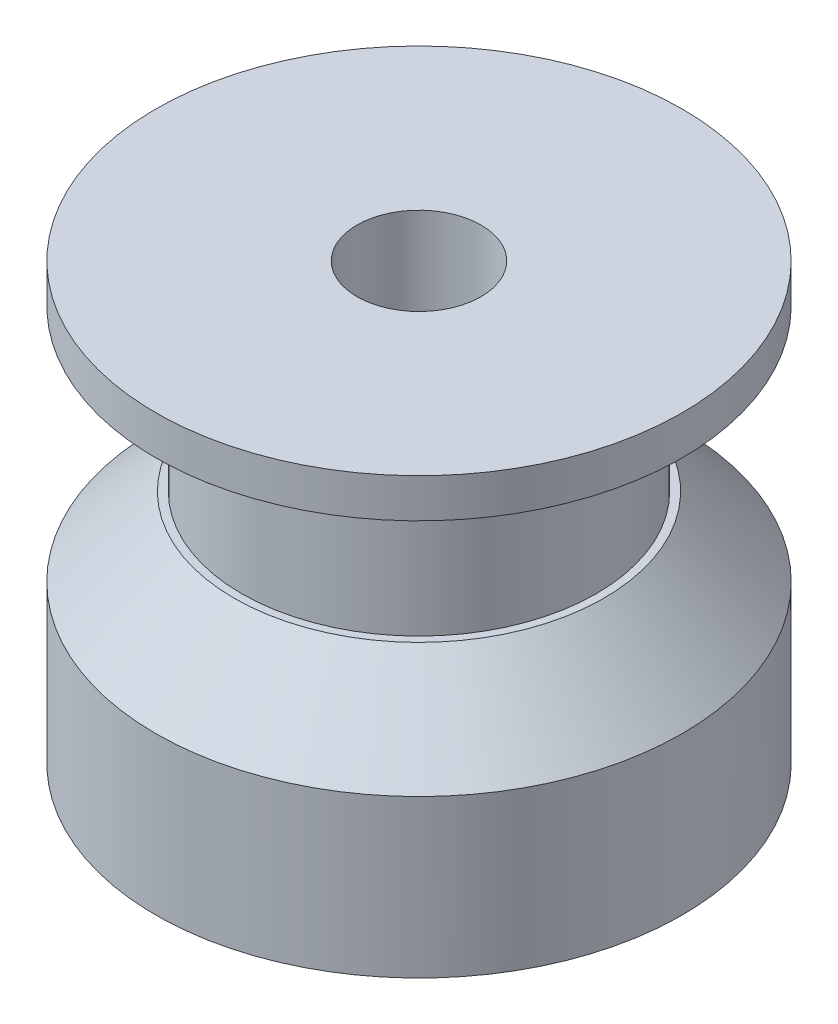
SolidWorks part; units mm, degrees
material "6061 Alloy"
ref_plane "Front Plane" through (0, 0, 0) normal (0, 0, 1) x (1, 0, 0)
ref_plane "Top Plane" through (0, 0, 0) normal (0, 1, 0) x (1, 0, 0)
ref_plane "Right Plane" through (0, 0, 0) normal (1, 0, 0) x (0, 0, -1)
sketch "Sketch1" plane through (0, 0, 0) normal (0, 0, 1) x (1, 0, 0)
  line L0 (0, 0) -> (0, 16.6392) construction
  line L1 (0, 0) -> (31.4533, 0) construction
  line L2 (1.5875, 0) -> (1.5875, 11.1252)
  line L3 (1.5875, 11.1252) -> (6.73, 11.1252)
  line L4 (6.73, 11.1252) -> (6.73, 10.1252)
  line L5 (6.73, 10.1252) -> (4.5339, 10.1252)
  line L6 (4.5339, 10.1252) -> (4.5339, 6.0198)
  line L7 (4.5339, 6.0198) -> (6.731, 6.0198)
  line L8 (6.731, 6.0198) -> (6.731, 0)
  line L9 (6.731, 0) -> (1.5875, 0)
  dimension "D1" = 6.731
  dimension "D2" = 1.5875
  dimension "D3" = 11.1252
  dimension "D4" = 1
  dimension "D5" = 5.1054
  dimension "D6" = 4.5339
  dimension "D7" = 6.73
revolve "Revolve1" add sketch "Sketch1" angle 360 about L0
chamfer "Chamfer1" distance 2 angle 45 1 edges at (0, 6.0198, -6.731)
hole_wizard "M2x0.4 Tapped Hole1" positions "Sketch2" profile "Sketch4" tap size "M2x0.4" standard "ANSI Metric"
sketch "Sketch2" plane through (0, 0, 0) normal (0, -1, 0) x (-1, 0, 0)
  line L0 (0, 0) -> (0, -6.731) construction
  circle A0 centre (0, 0) radius 6.731 construction
  point P0 (0, -4.9773)
  point P16 (-4.9773, 0)
  point P17 (0, 4.9773)
  point P18 (4.9773, 0)
  point P19 (0, 0)
  dimension "D1" = 4.9773
  dimension "D2" = 4
sketch "Sketch4" plane through (0, 0, 4.9773) normal (1, 0, 0) x (0, 0, -1)
  line L0 (0, 0) -> (0, 3.4807)
  line L1 (0, 3.4807) -> (0.8, 3)
  line L2 (0.8, 3) -> (0.8, 0)
  line L5 (0.8, 0) -> (0, 0)
  line L10 (0, 3.4807) -> (-0.8, 3) construction
  line L11 (0, -6.35) -> (0, 107.95) construction
  dimension "Tap Drill Dia." = 1.6
  dimension "Tap Drill Depth" = 3
  dimension "Drill Angle" = 118
cosmetic thread "Hole Thread1" parameters "D1"=3, "D2"=2
cosmetic thread "Hole Thread2" parameters "D1"=3, "D2"=2
cosmetic thread "Hole Thread3" parameters "D1"=3, "D2"=2
cosmetic thread "Hole Thread4" parameters "D1"=3, "D2"=2
